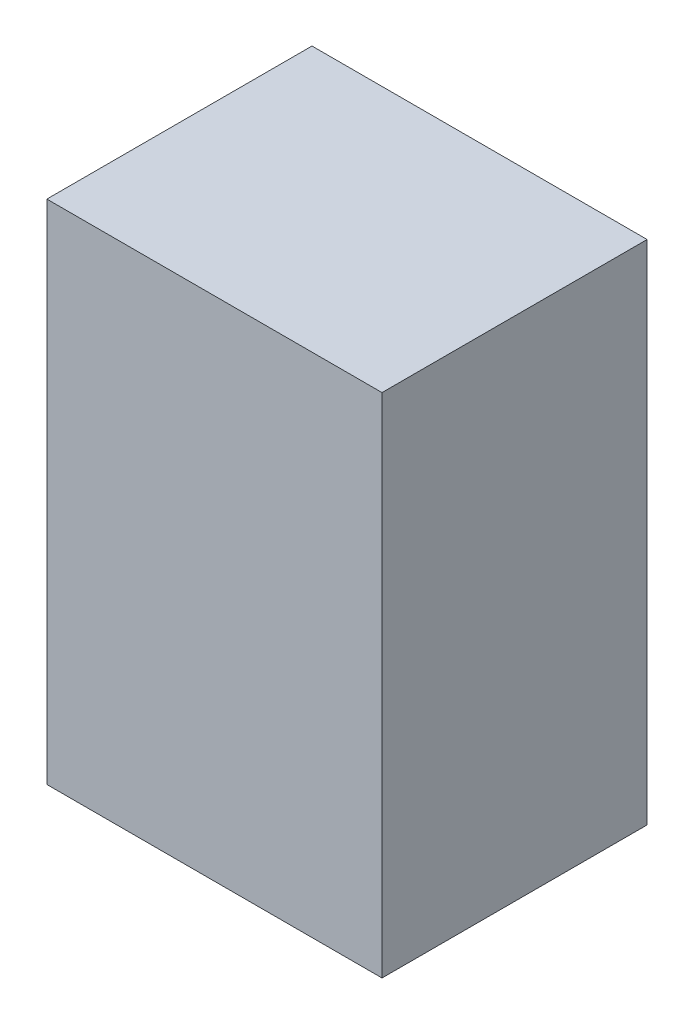
SolidWorks part; units mm, degrees
ref_plane "前视基准面" through (0, 0, 0) normal (0, 0, 1) x (1, 0, 0)
ref_plane "上视基准面" through (0, 0, 0) normal (0, 1, 0) x (1, 0, 0)
ref_plane "右视基准面" through (0, 0, 0) normal (1, 0, 0) x (0, 0, -1)
sketch "草图1" plane through (0, 0, 0) normal (0, 1, 0) x (1, 0, 0)
  line L1 (-55.9097, 46.2078) -> (10.1953, 46.2078)
  line L2 (-55.9097, 46.2078) -> (-55.9097, -6.0843)
  line L3 (-55.9097, -6.0843) -> (10.1953, -6.0843)
  line L4 (10.1953, 46.2078) -> (10.1953, -6.0843)
  line L5 (-55.9097, 46.2078) -> (10.1953, -6.0843) construction
  line L6 (-55.9097, -6.0843) -> (10.1953, 46.2078) construction
  point P0 (-22.8572, 20.0617)
extrude "凸台-拉伸1" add sketch "草图1" along normal blind 100 contours L1 L4 L3 L2
